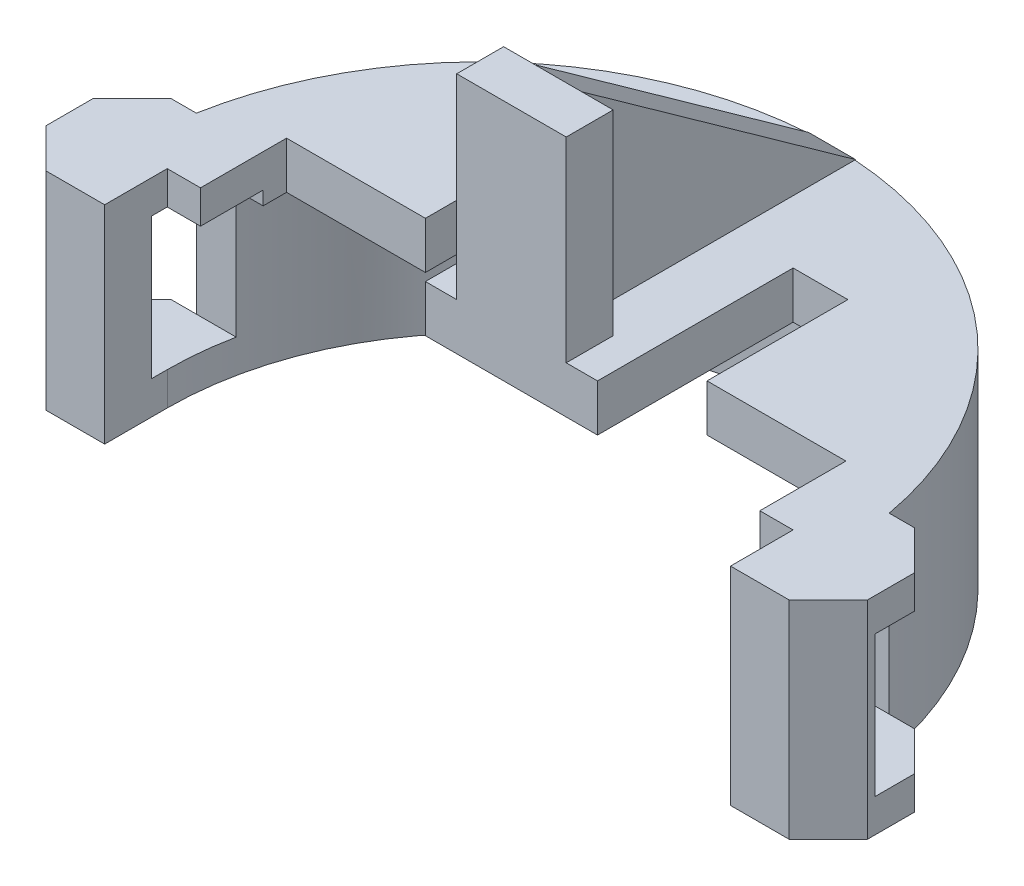
SolidWorks part; units mm, degrees
ref_plane "Front Plane" through (0, 0, 0) normal (0, 0, 1) x (1, 0, 0)
ref_plane "Top Plane" through (0, 0, 0) normal (0, 1, 0) x (1, 0, 0)
ref_plane "Right Plane" through (0, 0, 0) normal (1, 0, 0) x (0, 0, -1)
sketch "Sketch1" plane through (0, 0, 0) normal (0, 0, 1) x (1, 0, 0)
  line L0 (0, 0) -> (9, 0)
  line L1 (9, 0) -> (9, 5.3)
  line L2 (9, 5.3) -> (8, 5.3)
  line L3 (8, 5.3) -> (8, 0)
  line L4 (9, 4.1) -> (0, 4.1)
  line L5 (0, 4.1) -> (0, 5.3)
  line L6 (0, 5.3) -> (8, 5.3)
  line L7 (0, 0) -> (0, 2.65) construction
  dimension "D1" = 9
  dimension "D2" = 5.3
  dimension "D3" = 1
  dimension "D4" = 1.2
revolve "Revolve1" add sketch "Sketch1" angle 180 about L7
sketch "Sketch2" plane through (0, 0, 0) normal (0, 0, 1) x (1, 0, 0)
  line L0 (-8, 4.1) -> (8, 4.1) construction
  line L1 (-3.105, 4.1) -> (3.105, 4.1)
  line L2 (-3.105, 4.1) -> (-3.105, 2.6)
  line L3 (-3.105, 2.6) -> (3.105, 2.6)
  line L4 (3.105, 4.1) -> (3.105, 2.6)
  line L5 (-3.105, 4.1) -> (3.105, 2.6) construction
  line L6 (-3.105, 2.6) -> (3.105, 4.1) construction
  point P0 (0, 3.35)
  dimension "D1" = 6.21
  dimension "D2" = 1.5
  dimension "D3" = 0
  dimension "D4" = 0
extrude "Cut-Extrude1" cut sketch "Sketch2" against normal through all
sketch "Sketch3" plane through (0, 5.3, 0) normal (0, 1, 0) x (1, 0, 0)
  line L0 (9, 0) -> (-9, 0) construction
  line L1 (-3.6, 5.8) -> (3.6, 5.8)
  line L2 (-3.6, 5.8) -> (-3.6, 0)
  line L3 (-3.6, 0) -> (3.6, 0)
  line L4 (3.6, 5.8) -> (3.6, 0)
  line L5 (-3.6, 5.8) -> (3.6, 0) construction
  line L6 (-3.6, 0) -> (3.6, 5.8) construction
  line L8 (-2.2, 5.8) -> (2.2, 5.8)
  line L9 (-2.2, 5.8) -> (-2.2, 0.8)
  line L10 (-2.2, 0.8) -> (2.2, 0.8)
  line L11 (2.2, 5.8) -> (2.2, 0.8)
  line L12 (-2.2, 5.8) -> (2.2, 0.8) construction
  line L13 (-2.2, 0.8) -> (2.2, 5.8) construction
  point P0 (0, 2.9)
  point P8 (0, 3.3)
  line M9 (-9, 0) -> (9, 0)
  dimension "D1" = 7.2
  dimension "D2" = 5.8
  dimension "D3" = 0
  dimension "D4" = 0
  dimension "D5" = 4.4
  dimension "D6" = 5
  dimension "D7" = 0
  dimension "D8" = 0
extrude "Cut-Extrude2" cut sketch "Sketch3" against normal through all contours L1 L11 L10 L9 L2 L4 M9
sketch "Sketch4" plane through (0, 5.3, 0) normal (0, 1, 0) x (1, 0, 0)
  line L1 (3.6, 0) -> (7, 0)
  line L2 (3.6, 0) -> (3.6, -2)
  line L3 (3.6, -2) -> (7, -2)
  line L4 (7, 0) -> (7, -2)
  line L5 (-3.6, 0) -> (-7, 0)
  line L6 (-3.6, 0) -> (-3.6, -2)
  line L7 (-3.6, -2) -> (-7, -2)
  line L8 (-7, 0) -> (-7, -2)
  dimension "D1" = 3.4
  dimension "D2" = 3.4
  dimension "D3" = 2
  dimension "D4" = 2
extrude "Boss-Extrude1" add sketch "Sketch4" against normal blind 1.2
ref_plane "Plane1" through (8, 0, 0) normal (1, 0, 0) x (0, 0, -1)
sketch "Sketch5" plane through (8, 0, 0) normal (1, 0, 0) x (0, 0, -1)
  line L1 (1.6, 5.3) -> (-1.6, 5.3)
  line L2 (1.6, 5.3) -> (1.6, 0)
  line L3 (1.6, 0) -> (-1.6, 0)
  line L4 (-1.6, 5.3) -> (-1.6, 0)
  line L5 (-1.6, 5.3) -> (1.6, 0) construction
  line L6 (1.6, 5.3) -> (-1.6, 0) construction
  line L7 (0, 0) -> (0, 5.3) construction
  point P6 (0, 2.65)
  dimension "D1" = 2.65
  dimension "D2" = 5.3
  dimension "D3" = 3.2
  dimension "D4" = 0
sketch "Sketch6" plane through (0, 0, -0.8) normal (0, 0, 1) x (1, 0, 0)
  line L0 (-2.2, 5.3) -> (2.2, 5.3) construction
  line L1 (1.4, 5.3) -> (-1.4, 5.3)
  line L2 (1.4, 5.3) -> (1.4, 10.3)
  line L3 (1.4, 10.3) -> (-1.4, 10.3)
  line L4 (-1.4, 5.3) -> (-1.4, 10.3)
  line L5 (-1.4, 10.3) -> (1.4, 5.3) construction
  line L6 (-1.4, 5.3) -> (1.4, 10.3) construction
  point P6 (0, 7.8)
  dimension "D1" = 0
  dimension "D2" = 5
  dimension "D3" = 2.8
extrude "Boss-Extrude3" add sketch "Sketch6" against normal blind 1.2 contours L4 L3 L2 L1
sketch "Sketch7" plane through (0, 0, 0) normal (1, 0, 0) x (0, 0, -1)
  line L0 (2, 10.3) -> (9, 5.3)
  line L1 (9, 5.3) -> (0, 5.3) construction
  line L2 (9, 5.3) -> (2, 5.3)
  line L3 (2, 5.3) -> (2, 10.3)
extrude "Boss-Extrude4" add sketch "Sketch7" along normal mid plane 1.2
sketch "Sketch8" plane through (0, 5.3, 0) normal (0, 1, 0) x (1, 0, 0)
  line L1 (-7.15, 2.2) -> (7.15, 2.2)
  line L2 (-7.15, 2.2) -> (-7.15, 0)
  line L3 (-7.15, 0) -> (7.15, 0)
  line L4 (7.15, 2.2) -> (7.15, 0)
  line L5 (-7.15, 2.2) -> (7.15, 0) construction
  line L6 (-7.15, 0) -> (7.15, 2.2) construction
  line L7 (-2.5, 0) -> (2.5, 0)
  line L8 (-2.5, 0) -> (-2.5, 2.2)
  line L9 (-2.5, 2.2) -> (2.5, 2.2)
  line L10 (2.5, 0) -> (2.5, 2.2)
  line L11 (-2.5, 0) -> (2.5, 2.2) construction
  line L12 (-2.5, 2.2) -> (2.5, 0) construction
  line L13 (-7.15, 0) -> (9.555, 0)
  line L14 (-7.15, 0) -> (-7.15, -4.4024)
  line L15 (-7.15, -4.4024) -> (9.555, -4.4024)
  line L16 (9.555, 0) -> (9.555, -4.4024)
  point P0 (0, 1.1)
  point P5 (-7.15, 1.1)
  point P7 (0, 1.1)
  line M8 (-9, 0) -> (-7, 0)
  line M11 (-3.6, -2) -> (-3.6, 5.8)
  dimension "D1" = 0
  dimension "D2" = 0
  dimension "D3" = 2.2
  dimension "D4" = 14.3
  dimension "D5" = 5
  dimension "D6" = 16.705
  dimension "D7" = 4.4024
extrude "Cut-Extrude3" cut sketch "Sketch8" against normal blind 10 contours L3 L1 L2 M8 M11 | L10 L3 L4 L1 | L14 L13 L16 L15
extrude "Boss-Extrude5" add sketch "Sketch5" along normal blind 2.5 contours L4 L3 L2 L1
sketch "Sketch9" plane through (10.5, 0, 0) normal (1, 0, 0) x (0, 0, -1)
  line L0 (-1.6, 5.3) -> (1.6, 0) construction
  line L1 (-0.4, 4.45) -> (1.6, 4.45)
  line L2 (-0.4, 4.45) -> (-0.4, 0.85)
  line L3 (-0.4, 0.85) -> (1.6, 0.85)
  line L4 (1.6, 4.45) -> (1.6, 0.85)
  line L5 (-0.4, 4.45) -> (1.6, 0.85) construction
  line L6 (-0.4, 0.85) -> (1.6, 4.45) construction
  line L7 (1.6, 5.3) -> (-1.6, 0) construction
  line L8 (1.6, 5.3) -> (1.6, 0) construction
  line L9 (-1.6, 5.3) -> (-1.6, 0) construction
  point P0 (0.6, 2.65)
  point P15 (0, 2.65)
  dimension "D1" = 0
  dimension "D2" = 0
  dimension "D3" = 1.2
  dimension "D4" = 3.6
extrude "Cut-Extrude4" cut sketch "Sketch9" against normal blind 5
mirror "Mirror1" about plane through (0, 0, 0) normal (1, 0, 0) of "Boss-Extrude5", "Cut-Extrude4"
chamfer "Chamfer1" distance 1 angle 45 6 edges at (-10.5, 0.425, -1.6) (-10.5, 4.875, -1.6) (-10.5, 2.65, 1.6) (10.5, 0.425, -1.6) (10.5, 4.875, -1.6) (10.5, 2.65, 1.6)
